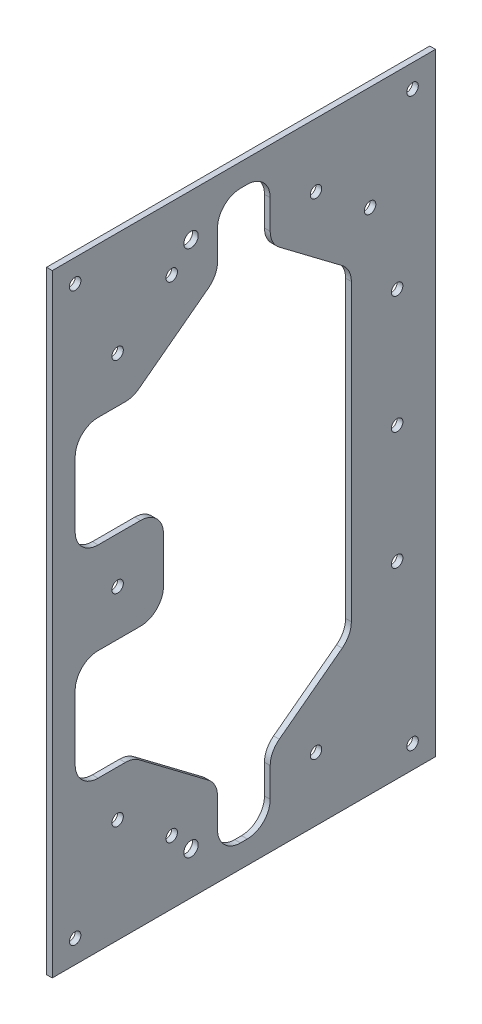
SolidWorks part; units mm, degrees
material "6061-T6 (SS)"
ref_plane "Front Plane" through (0, 0, 0) normal (0, 0, 1) x (1, 0, 0)
ref_plane "Top Plane" through (0, 0, 0) normal (0, 1, 0) x (1, 0, 0)
ref_plane "Right Plane" through (0, 0, 0) normal (1, 0, 0) x (0, 0, -1)
sketch "Sketch1" plane through (0, 0, 0) normal (1, 0, 0) x (0, 0, -1)
  line L0 (0, -169.8625) -> (212.5, -169.8625) construction
  line L1 (0, 0) -> (212.5, 0)
  line L2 (0, 0) -> (0, -339.725)
  line L3 (0, -339.725) -> (212.5, -339.725)
  line L4 (212.5, 0) -> (212.5, -339.725)
  line L5 (153.5, -35.2425) -> (59, -35.2425) construction
  line L6 (191.25, -104.5325) -> (191.25, -169.8625) construction
  line L7 (13.5, -50.2425) -> (59, -50.2425) construction
  line L8 (36.25, -50.2425) -> (36.25, -169.8625) construction
  line L9 (106.25, 0) -> (106.25, -339.725) construction
  line L10 (173.5, -104.5325) -> (191.25, -104.5325) construction
  circle A0 centre (12.7, -12.7) radius 3.175
  circle A1 centre (199.8, -12.7) radius 3.175
  circle A2 centre (66.25, -35.2425) radius 3.175
  circle A3 centre (146.25, -35.2425) radius 3.175
  circle A4 centre (176.25, -57.8625) radius 3.175
  circle A5 centre (36.25, -57.8625) radius 3.175
  circle A6 centre (191.25, -104.5325) radius 3.175
  circle A7 centre (36.25, -169.8625) radius 3.175
  circle A8 centre (191.25, -169.8625) radius 3.175
  circle A9 centre (36.25, -281.8625) radius 3.175
  circle A10 centre (66.25, -304.4825) radius 3.175
  circle A11 centre (12.7, -327.025) radius 3.175
  circle A12 centre (199.8, -327.025) radius 3.175
  circle A13 centre (146.25, -304.4825) radius 3.175
  circle A14 centre (191.25, -235.1925) radius 3.175
  dimension "D1" = 339.725
  dimension "D2" = 212.5
  dimension "D3" = 40
  dimension "D4" = 112
  dimension "D5" = 85
  dimension "D6" = 157.1625
extrude "Boss-Extrude1" add sketch "Sketch1" along normal blind 3.175
sketch "Sketch2" plane through (3.175, 0, 0) normal (1, 0, 0) x (0, 0, -1)
  line L1 (165.85, -88.1617) -> (165.85, -251.5633)
  line L4 (0, 0) -> (0, -339.725)
  line L5 (0, -339.725) -> (212.5, -339.725)
  line L6 (212.5, -339.725) -> (212.5, 0)
  line L7 (212.5, 0) -> (0, 0)
  line L8 (0, 0) -> (0, -339.725)
  line L9 (0, -339.725) -> (212.5, -339.725)
  line L10 (212.5, -339.725) -> (212.5, 0)
  line L11 (212.5, 0) -> (0, 0)
  line L14 (25.4, -144.4625) -> (48.95, -144.4625)
  line L15 (25.4, -83.2625) -> (40.5014, -83.2625)
  line L16 (12.7, -95.9625) -> (12.7, -131.7625)
  line L17 (34.7163, -60.6425) -> (37.7837, -60.6425)
  line L18 (61.65, -70.5625) -> (61.65, -70.522)
  line L19 (61.65, -182.5625) -> (61.65, -157.1625)
  line L20 (36.25, -57.8625) -> (66.25, -35.2425) construction
  line L21 (48.1473, -80.703) -> (86.5959, -51.7127)
  line L22 (91.65, -25.4) -> (91.65, -41.5722)
  line L23 (120.85, -25.4) -> (120.85, -41.5722)
  line L24 (104.35, -12.7) -> (108.15, -12.7)
  line L25 (176.25, -57.8625) -> (146.25, -35.2425) construction
  line L26 (125.9041, -51.7127) -> (160.7959, -78.0212)
  line L27 (0, -169.8625) -> (212.5, -169.8625) construction
  line L28 (176.25, -281.8625) -> (146.25, -304.4825) construction
  line L29 (36.25, -281.8625) -> (66.25, -304.4825) construction
  line L30 (125.9041, -288.0123) -> (160.7959, -261.7038)
  line L31 (104.35, -327.025) -> (108.15, -327.025)
  line L32 (120.85, -314.325) -> (120.85, -298.1528)
  line L33 (91.65, -314.325) -> (91.65, -298.1528)
  line L34 (48.1473, -259.022) -> (86.5959, -288.0123)
  line L35 (61.65, -269.1625) -> (61.65, -269.203)
  line L36 (34.7163, -279.0825) -> (37.7837, -279.0825)
  line L37 (12.7, -243.7625) -> (12.7, -207.9625)
  line L38 (25.4, -256.4625) -> (40.5014, -256.4625)
  line L39 (25.4, -195.2625) -> (48.95, -195.2625)
  circle A0 centre (176.25, -57.8625) radius 3.175 construction
  circle A1 centre (146.25, -35.2425) radius 3.175 construction
  circle A2 centre (66.25, -35.2425) radius 3.175 construction
  circle A3 centre (36.25, -57.8625) radius 3.175 construction
  circle A4 centre (36.25, -169.8625) radius 3.175 construction
  circle A5 centre (36.25, -281.8625) radius 3.175 construction
  circle A6 centre (66.25, -304.4825) radius 3.175 construction
  circle A7 centre (146.25, -304.4825) radius 3.175 construction
  circle A8 centre (191.25, -235.1925) radius 3.175 construction
  circle A9 centre (191.25, -169.8625) radius 3.175 construction
  circle A10 centre (191.25, -104.5325) radius 3.175 construction
  circle A11 centre (176.25, -57.8625) radius 3.175 construction
  circle A12 centre (146.25, -35.2425) radius 3.175 construction
  circle A13 centre (66.25, -35.2425) radius 3.175 construction
  circle A14 centre (36.25, -57.8625) radius 3.175 construction
  circle A15 centre (36.25, -169.8625) radius 3.175 construction
  circle A16 centre (36.25, -281.8625) radius 3.175 construction
  circle A17 centre (66.25, -304.4825) radius 3.175 construction
  circle A18 centre (146.25, -304.4825) radius 3.175 construction
  circle A19 centre (191.25, -235.1925) radius 3.175 construction
  circle A20 centre (191.25, -169.8625) radius 3.175 construction
  circle A21 centre (191.25, -104.5325) radius 3.175 construction
  arc A28 (48.95, -144.4625) -> (61.65, -157.1625) centre (48.95, -157.1625) cw
  arc A29 (12.7, -131.7625) -> (25.4, -144.4625) centre (25.4, -131.7625) ccw
  arc A30 (12.7, -95.9625) -> (25.4, -83.2625) centre (25.4, -95.9625) cw
  arc A33 (165.85, -88.1617) -> (160.7959, -78.0212) centre (153.15, -88.1617) ccw
  arc A34 (125.9041, -51.7127) -> (120.85, -41.5722) centre (133.55, -41.5722) cw
  arc A35 (108.15, -12.7) -> (120.85, -25.4) centre (108.15, -25.4) cw
  arc A36 (104.35, -12.7) -> (91.65, -25.4) centre (104.35, -25.4) ccw
  arc A37 (86.5959, -51.7127) -> (91.65, -41.5722) centre (78.95, -41.5722) ccw
  arc A38 (48.1473, -80.703) -> (40.5014, -83.2625) centre (40.5014, -70.5625) cw
  circle A39 centre (36.25, -281.8625) radius 3.175 construction
  circle A40 centre (66.25, -304.4825) radius 3.175 construction
  circle A41 centre (146.25, -304.4825) radius 3.175 construction
  circle A42 centre (176.25, -281.8625) radius 3.175 construction
  arc A43 (48.1473, -259.022) -> (40.5014, -256.4625) centre (40.5014, -269.1625) ccw
  arc A44 (86.5959, -288.0123) -> (91.65, -298.1528) centre (78.95, -298.1528) cw
  arc A45 (104.35, -327.025) -> (91.65, -314.325) centre (104.35, -314.325) cw
  arc A46 (108.15, -327.025) -> (120.85, -314.325) centre (108.15, -314.325) ccw
  arc A47 (125.9041, -288.0123) -> (120.85, -298.1528) centre (133.55, -298.1528) ccw
  arc A48 (165.85, -251.5633) -> (160.7959, -261.7038) centre (153.15, -251.5633) cw
  arc A49 (12.7, -243.7625) -> (25.4, -256.4625) centre (25.4, -243.7625) ccw
  arc A50 (12.7, -207.9625) -> (25.4, -195.2625) centre (25.4, -207.9625) cw
  arc A51 (48.95, -195.2625) -> (61.65, -182.5625) centre (48.95, -182.5625) ccw
  point P73 (61.65, -83.2625)
  point P78 (61.65, -60.6425)
  point P92 (61.65, -279.0825)
  point P110 (61.65, -169.8625)
  point P114 (165.85, -169.8625)
  point P115 (61.65, -256.4625)
  dimension "D11" = 25.4
  dimension "D13" = 25.4
  dimension "D17" = 12.7
  dimension "D2" = 25.4
  dimension "D7" = 25.4
  dimension "D8" = 25.4
  dimension "D9" = 25.4
  dimension "D14" = 25.4
  dimension "D15" = 12.7
  dimension "D16" = 25.4
  dimension "D1" = 0
extrude "Cut-Extrude1" cut sketch "Sketch2" against normal through all
sketch "Sketch3" plane through (0, 0, 0) normal (-1, 0, 0) x (0, 0, 1)
  line L0 (-99.95, -11.9115) -> (-99.95, -342.1115) construction
  line L1 (-99.95, -11.9115) -> (-99.95, -342.1115)
  line L3 (-303.15, -342.1115) -> (-99.95, -342.1115) construction
  circle A0 centre (-76.95, -316.1115) radius 4
  dimension "D2" = 26
  dimension "D3" = 8
  dimension "D1" = 23
extrude "Cut-Extrude2" cut sketch "Sketch3" against normal blind 45.72 contours A0
sketch "Sketch4" plane through (0, 0, 0) normal (-1, 0, 0) x (0, 0, 1)
  circle A0 centre (-76.9625, -23.6135) radius 4 construction
  circle A1 centre (-76.9625, -23.6135) radius 4
extrude "Cut-Extrude3" cut sketch "Sketch4" against normal blind 14.986
